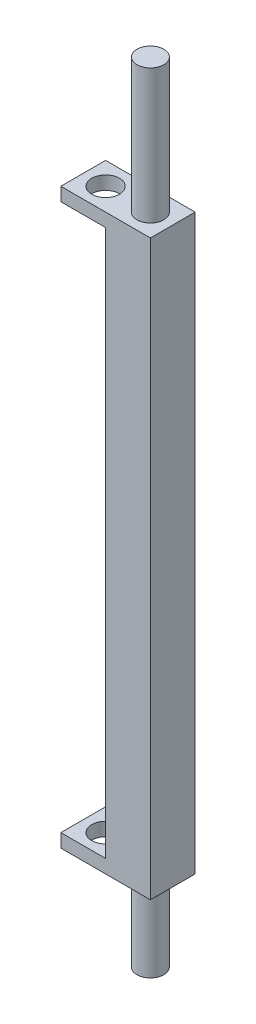
SolidWorks part; units mm, degrees
ref_plane "前视基准面" through (0, 0, 0) normal (0, 0, 1) x (1, 0, 0)
ref_plane "上视基准面" through (0, 0, 0) normal (0, 1, 0) x (1, 0, 0)
ref_plane "右视基准面" through (0, 0, 0) normal (1, 0, 0) x (0, 0, -1)
other "Configuration Table"
sketch "草图2" plane through (0, 0, 0) normal (0, 1, 0) x (1, 0, 0)
  line L1 (5, -2.5) -> (-5, -2.5)
  line L2 (5, -2.5) -> (5, 2.5)
  line L3 (5, 2.5) -> (-5, 2.5)
  line L4 (-5, -2.5) -> (-5, 2.5)
  line L5 (5, -2.5) -> (-5, 2.5) construction
  line L6 (5, 2.5) -> (-5, -2.5) construction
  circle A0 centre (2.5, 0) radius 1.55
  circle A1 centre (-2.5, 0) radius 1.55
  point P0 (0, 0)
  dimension "D3" = 3.1
  dimension "D4" = 3.1
  dimension "D1" = 10
  dimension "D2" = 2.5
  dimension "D5" = 2.5
  dimension "D6" = 5
extrude "凸台-拉伸1" add sketch "草图2" along normal blind 1.5 contours L3 L4 L1 L2
sketch "草图3" plane through (0, 0, 0) normal (0, -1, 0) x (1, 0, 0)
  line L0 (5, -2.5) -> (-5, -2.5) construction
  circle A0 centre (-2.5, 0) radius 1.55
  dimension "D3" = 3.1
  dimension "D1" = 2.5
  dimension "D2" = 2.5
extrude "切除-拉伸1" cut sketch "草图3" against normal blind 1.5
sketch "草图4" plane through (0, 0, 0) normal (0, -1, 0) x (1, 0, 0)
  line L0 (0, 2.5) -> (0, -2.5)
  line L1 (5, 2.5) -> (-5, 2.5) construction
  line L2 (5, -2.5) -> (-5, -2.5) construction
  line L3 (0, -2.5) -> (5, -2.5)
  line L4 (5, -2.5) -> (5, 2.5)
  line L5 (5, 2.5) -> (0, 2.5)
  dimension "D1" = 5
extrude "凸台-拉伸2" add sketch "草图4" along normal blind 61
sketch "草图5" plane through (0, -61, 0) normal (0, -1, 0) x (1, 0, 0)
  line L1 (5, 2.5) -> (-5, 2.5)
  line L2 (5, 2.5) -> (5, -2.5)
  line L3 (5, -2.5) -> (-5, -2.5)
  line L4 (-5, 2.5) -> (-5, -2.5)
extrude "凸台-拉伸3" add sketch "草图5" along normal blind 1.5
sketch "草图6" plane through (0, -62.5, 0) normal (0, -1, 0) x (1, 0, 0)
  line L0 (-5, 2.5) -> (-5, -2.5) construction
  circle A0 centre (-2.5, 0) radius 1.55
  dimension "D2" = 3.1
  dimension "D1" = 2.5
extrude "切除-拉伸2" cut sketch "草图6" against normal blind 1.5
sketch "草图7" plane through (0, 1.5, 0) normal (0, 1, 0) x (1, 0, 0)
  line L0 (5, -2.5) -> (5, 2.5) construction
  line L1 (5, -2.5) -> (-5, -2.5) construction
  circle A0 centre (2.5, 0) radius 1.5
  dimension "D1" = 3
  dimension "D2" = 2.5
  dimension "D3" = 2.5
extrude "凸台-拉伸4" add sketch "草图7" along normal blind 15 contours A0
sketch "草图11" plane through (0, -62.5, 0) normal (0, -1, 0) x (1, 0, 0)
  line L0 (-5, -2.5) -> (5, -2.5) construction
  line L1 (5, -2.5) -> (5, 2.5) construction
  circle A0 centre (2.5, 0) radius 1.5
  dimension "D3" = 3
  dimension "D1" = 2.5
  dimension "D2" = 2.5
extrude "凸台-拉伸5" add sketch "草图11" along normal blind 9
